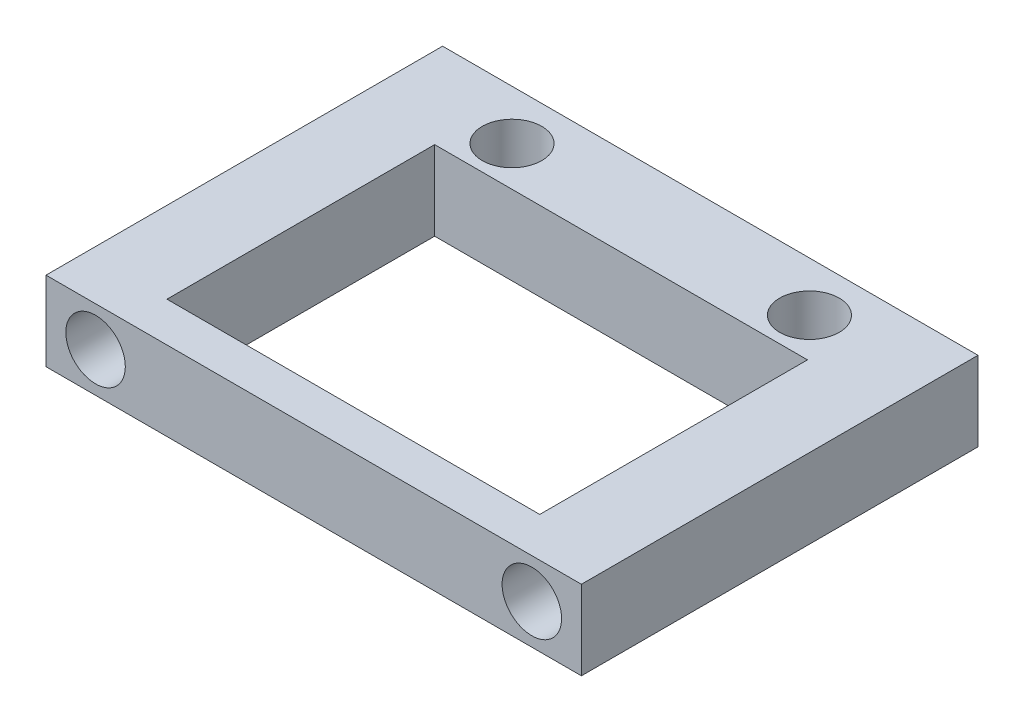
SolidWorks part; units mm, degrees
other "Camera1"
ref_plane "Front Plane" through (0, 0, 0) normal (0, 0, 1) x (1, 0, 0)
ref_plane "Top Plane" through (0, 0, 0) normal (0, 1, 0) x (1, 0, 0)
ref_plane "Right Plane" through (0, 0, 0) normal (1, 0, 0) x (0, 0, -1)
sketch "Sketch1" plane through (0, 0, 0) normal (0, 1, 0) x (1, 0, 0)
  line L0 (0, 0) -> (0, 20.6962) construction
  line L1 (-13.5, -8.75) -> (13.5, -8.75)
  line L2 (-13.5, -8.75) -> (-13.5, 11.25)
  line L3 (-13.5, 11.25) -> (13.5, 11.25)
  line L4 (13.5, -8.75) -> (13.5, 11.25)
  line L6 (-9.4, -6.75) -> (9.4, -6.75)
  line L7 (-9.4, -6.75) -> (-9.4, 6.75)
  line L8 (-9.4, 6.75) -> (9.4, 6.75)
  line L9 (9.4, -6.75) -> (9.4, 6.75)
  circle A0 centre (-7.5, 8.75) radius 1.5
  circle A1 centre (7.5, 8.75) radius 1.5
  point P0 (0, 0)
  point P12 (0, 0)
  dimension "D2" = 3
  dimension "D4" = 7.5
  dimension "D1" = 27
  dimension "5" = 20
  dimension "D3" = 2.5
  dimension "D5" = 2
  dimension "D6" = 13.5
  dimension "D7" = 4.1
  dimension "D8" = 4.1
extrude "Boss-Extrude1" add sketch "Sketch1" along normal blind 4
sketch "Sketch2" plane through (0, 0, -11.25) normal (0, 0, -1) x (-1, 0, 0)
  line L0 (13.5, 4) -> (13.5, 0) construction
  line L1 (-13.5, 4) -> (-13.5, 0) construction
  circle A0 centre (11, 2) radius 1.5
  circle A1 centre (-11, 2) radius 1.5
  point P8 (13.5, 2)
  point P12 (-13.5, 2)
  dimension "D1" = 3
  dimension "D2" = 3
  dimension "D3" = 22
  dimension "D4" = 2.5
  dimension "D5" = 2.5
sketch "Sketch5" plane through (0, 0, 8.75) normal (0, 0, 1) x (1, 0, 0)
  line L0 (13.5, 4) -> (13.5, 0) construction
  line L1 (-13.5, 4) -> (-13.5, 0) construction
  circle A0 centre (11, 2) radius 1.5
  circle A1 centre (-11, 2) radius 1.5
  point P9 (-13.5, 2)
  point P12 (13.5, 2)
  dimension "D1" = 2.5
  dimension "D2" = 2.5
extrude "Cut-Extrude2" cut sketch "Sketch2" against normal blind 6
extrude "Cut-Extrude3" cut sketch "Sketch5" against normal blind 6
